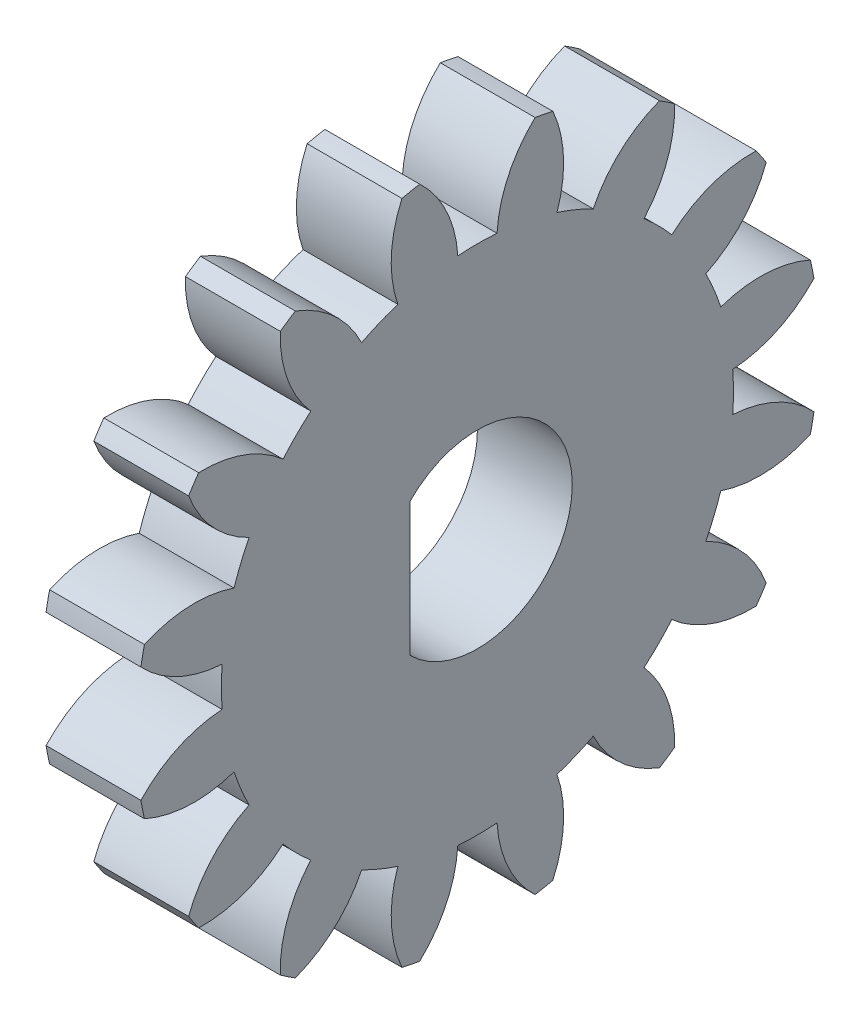
SolidWorks part; units mm, degrees
ref_plane "Plane1" through (0, 0, 0) normal (0, 0, 1) x (1, 0, 0)
ref_plane "Plane2" through (0, 0, 0) normal (0, 1, 0) x (1, 0, 0)
ref_plane "Plane3" through (0, 0, 0) normal (1, 0, 0) x (0, 0, -1)
other "Configuration Table"
sketch "HoldingSke" plane through (0, 0, 0) normal (0, 1, 0) x (1, 0, 0)
  line L0 (0, 0) -> (0.4806, -0.1378)
  line L1 (-15, 0) -> (100, 0) construction
  line L2 (0, 0) -> (-2.1039, 2.3779)
  line L3 (0, 0) -> (-11.863, 4.5341)
  line L4 (0, 0) -> (8.3015, 2.3804)
  line L5 (0, 0) -> (-46.8476, -17.4728)
  line L6 (0, 0) -> (-4.1448, -2.7965)
  line L7 (-2.1039, 2.3779) -> (8.6586, 51.2059)
  line L8 (-76.2, 54.61) -> (-74.4, 54.61)
  line L9 (-71.009, 38.7566) -> (-53.1078, 45.2721)
  line L10 (-76.2, 71.12) -> (104.1128, 71.12)
  line L11 (0, 0) -> (-5, 0)
  line L12 (-76.2, 101.6) -> (-76.133, 101.6)
  line L13 (24.9733, 27.94) -> (52.9518, 28.4284)
  line L14 (24.9733, 27.94) -> (24.9743, 27.94)
  line L15 (24.9733, 27.94) -> (100.4006, 29.5858)
  line L16 (-63.627, -2) -> (-12.827, -2)
  circle A0 centre (0, 0) radius 5
  circle A1 centre (0, 0) radius 13.499
  circle A2 centre (0, 0) radius 37.5
  circle A3 centre (0, 0) radius 5
  dimension "MHD" = 26.998
  dimension "Hub_dia" = 75
  dimension "Bore" = 10
  dimension "MBD" = 10
  dimension "Num_teeth" = 16
  dimension "Pitch" = 0.5
  dimension "Overall_len" = 50
  dimension "Show_teeth" = 16
  dimension "Thickness" = 5
  dimension "OAL" = 50.0001
  dimension "T_dim" = 1.8
  dimension "Ap" = 20
  dimension "H" = 19.05
  dimension "Pitch_radius" = 180.3128
  dimension "Width" = 5
  dimension "Backlash" = 0.067
  dimension "Addendum_fac" = 1
  dimension "Dedendum_fac" = 1.25
  dimension "Clearance_fac" = 0.25
  dimension "Dedendum_add" = 0.001
  dimension "Module" = 2
sketch "BasProSke" plane through (0, 0, 0) normal (0, 1, 0) x (1, 0, 0)
  line L0 (-10, 0) -> (60, 0) construction
  line L1 (0, 0) -> (0, 18)
  line L2 (0, 0) -> (5, 0)
  line L3 (5, 0) -> (5, 18)
  line L4 (5, 18) -> (0, 18)
  dimension "Thickness" = 5
  dimension "Diameter" = 36
revolve "Base-Revolve" add sketch "BasProSke" angle 360 about L0
sketch "TooCutSke" plane through (0, 0, 0) normal (1, 0, 0) x (0, 0, -1)
  line L1 (0, 0) -> (0, 107) construction
  line L2 (0, 0) -> (-1.6854, 15.911) construction
  line L3 (0, 0) -> (-6.2172, 31.2558) construction
  line L4 (-1.6854, 15.911) -> (-3.1086, 15.6279) construction
  arc A0 (1.0343, 13.4593) -> (-1.0343, 13.4593) centre (0, 0) ccw
  arc A1 (3.0657, 17.7628) -> (-3.0657, 17.7628) centre (0, 0) ccw
  circle A2 centre (0, 0) radius 16 construction
  circle A3 centre (0, 0) radius 15.0351 construction
  arc A4 (-1.0343, 13.4593) -> (-3.0657, 17.7628) centre (-7.4228, 13.075) ccw
  arc A5 (3.0657, 17.7628) -> (1.0343, 13.4593) centre (7.4228, 13.075) ccw
  dimension "Root_dia" = 26.998
  dimension "Overcut_dia" = 36.0508
  dimension "Pitch_dia" = 32
  dimension "Base_dia" = 30.0702
  dimension "Flank_rad" = 6.4
  dimension "Half_ang" = 11.25
  dimension "Half_CT" = 1.451
extrude "ToothCut" cut sketch "TooCutSke" along normal through all
fillet "Breaks" [suppressed] radius 0.04
fillet "RootFillets" [suppressed] radius 0.501
pattern_circular "TeethCuts" count 16 every 22.5 about axis through (-10, 0, 0) along (1, 0, 0) of "ToothCut", "RootFillets", "Breaks"
sketch "HubNeaOneSke" plane through (0, 0, 0) normal (-1, 0, 0) x (0, 0, 1)
  circle A0 centre (0, 0) radius 13.499
  dimension "Diameter" = 26.998
extrude "HubNearOne" [suppressed] add sketch "HubNeaOneSke" along normal blind 45.0001
sketch "HubNeaBotSke" plane through (0, 0, 0) normal (-1, 0, 0) x (0, 0, 1)
  circle A0 centre (0, 0) radius 13.499
  dimension "Diameter" = 26.998
extrude "HubNearBoth" [suppressed] add sketch "HubNeaBotSke" along normal blind 22.5
ref_plane "FarPln" through (5, 0, 0) normal (1, 0, 0) x (0, 0, -1)
sketch "HubFarSke" plane through (5, 0, 0) normal (1, 0, 0) x (0, 0, -1)
  circle A0 centre (0, 0) radius 13.499
  dimension "Diameter" = 26.998
extrude "HubFar" [suppressed] add sketch "HubFarSke" along normal blind 22.5
sketch "BorSke" plane through (0, 0, 0) normal (1, 0, 0) x (0, 0, -1)
  circle A0 centre (0, 0) radius 5
  dimension "Diameter" = 10
extrude "Bore" cut sketch "BorSke" along normal mid plane 100.0001
sketch "KeySke" plane through (0, 0, 0) normal (1, 0, 0) x (0, 0, -1)
  line L0 (-2, 0) -> (-2, 6.8)
  line L1 (-2, 6.8) -> (2, 6.8)
  line L2 (2, 6.8) -> (2, 0)
  line L3 (0, 0) -> (0, 34) construction
  line L4 (-2, 0) -> (2, 0)
  dimension "Offset" = 6.8
  dimension "Width" = 4
extrude "Keyway" [suppressed] cut sketch "KeySke" along normal mid plane 100.0001
pattern_circular "Keyway2" [suppressed] count 2 every 90 about axis through (-10, 0, 0) along (1, 0, 0)
sketch "草图2" plane through (0, 0, 0) normal (-1, 0, 0) x (0, 0, 1)
  line L0 (3.5448, 3.5262) -> (3.5448, -3.5262)
  arc A0 (3.5448, -3.5262) -> (3.5448, 3.5262) centre (0, 0) ccw
extrude "凸台-拉伸1" add sketch "草图2" against normal up to surface (5 mm away) up to face at (5, 0, 5)
equation "' \"Module@HoldingSke\" = 6.35"
equation "' \"Num_teeth@HoldingSke\" = 12"
equation "' \"Ap@HoldingSke\" =  20"
equation "' \"Ap@HoldingSke\" = 20"
equation "' \"Width@HoldingSke\" = 0.5 * 25.4"
equation "' \"Hub_dia@HoldingSke\"= 1 * 25.4"
equation "' \"Hub_dia@HoldingSke\" = 1 * 25.4"
equation "' \"Overall_len@HoldingSke\" = 1.0 * 25.4"
equation "' \"Bore@HoldingSke\" = 0.75 * 25.4"
equation "' \"T_dim@HoldingSke\" = 0.1 * 25.4"
equation "' \"Width@KeySke\" = 0.25 * 25.4"
equation "' \"Show_teeth@HoldingSke\" = 13"
equation "' \"Backlash@HoldingSke\" = 0.009 * 25.4"
equation "' \"Addendum_fac@HoldingSke\" = 1.0"
equation "' \"Dedendum_fac@HoldingSke\" = 1.25"
equation "' \"Dedendum_add@HoldingSke\" = 0.00005 * 25.4"
equation "' \"Clearance_fac@HoldingSke\" = 0.25"
equation "\"Pitch@HoldingSke\" = 1 / \"Module@HoldingSke\""
equation "\"Overcut_dia@TooCutSke\" = (\"Num_teeth@HoldingSke\" + 2 * \"Addendum_fac@HoldingSke\") / \"Pitch@HoldingSke\" + 0.002 * 25.4"
equation "\"Pitch_dia@TooCutSke\" = \"Num_teeth@HoldingSke\" / \"Pitch@HoldingSke\""
equation "\"Base_dia@TooCutSke\" = \"Num_teeth@HoldingSke\" / \"Pitch@HoldingSke\" * cos((\"Ap@HoldingSke\"  * 3.14159265 / 180))"
equation "\"Root_dia@TooCutSke\" = (\"Num_teeth@HoldingSke\" + 2) / \"Pitch@HoldingSke\" - 2 * (\"Addendum_fac@HoldingSke\" + \"Dedendum_fac@HoldingSke\") / \"Pitch@HoldingSke\" - \"Dedendum_add@HoldingSke\" * 2"
equation "\"Half_ang@TooCutSke\" = 180 / \"Num_teeth@HoldingSke\""
equation "\"Half_CT@TooCutSke\" = \"Num_teeth@HoldingSke\" / \"Pitch@HoldingSke\" * sin((3.14159265 / 2 / \"Num_teeth@HoldingSke\")) / 2 - 7 * \"Backlash@HoldingSke\" / 4"
equation "\"Flank_rad@TooCutSke\" = \"Num_teeth@HoldingSke\" / \"Pitch@HoldingSke\" / 5"
equation "\"Radius@RootFillets\" = \"Clearance_fac@HoldingSke\" / \"Pitch@HoldingSke\" + \"Dedendum_add@HoldingSke\""
equation "\"Break_rad@Breaks\" = 0.02 / \"Pitch@HoldingSke\""
equation "\"Thickness@HoldingSke\" = \"Width@HoldingSke\""
equation "\"OAL@HoldingSke\" = \"Thickness@HoldingSke\""
equation "\"MHD@HoldingSke\" = (\"Num_teeth@HoldingSke\" + 2) / \"Pitch@HoldingSke\" - 2 * (\"Addendum_fac@HoldingSke\" + \"Dedendum_fac@HoldingSke\")  / \"Pitch@HoldingSke\" - \"Dedendum_add@HoldingSke\" * 2"
equation "\"MBD@HoldingSke\" = (\"Num_teeth@HoldingSke\" + 2) / \"Pitch@HoldingSke\" - 2 * (\"Addendum_fac@HoldingSke\" + \"Dedendum_fac@HoldingSke\")  / \"Pitch@HoldingSke\" - \"Dedendum_add@HoldingSke\" * 2 - 0.002 * 25.4"
equation "\"MHD@HoldingSke\" = ((sgn( \"MHD@HoldingSke\" - \"Hub_dia@HoldingSke\" )-1)*( \"MHD@HoldingSke\" - \"Hub_dia@HoldingSke\" ))/-2+ \"Hub_dia@HoldingSke\""
equation "\"MBD@HoldingSke\" = ((sgn( \"MBD@HoldingSke\" - \"Bore@HoldingSke\" )-1)*( \"MBD@HoldingSke\" - \"Bore@HoldingSke\" ))/-2+ \"Bore@HoldingSke\""
equation "\"OAL@HoldingSke\" = ((sgn( \"OAL@HoldingSke\" - \"Overall_len@HoldingSke\" )+1)*( \"OAL@HoldingSke\" - \"Overall_len@HoldingSke\" ))/2 + \"Overall_len@HoldingSke\" + 0.000002 * 25.4"
equation "\"Num_teeth@TeethCuts\" = int( \"Show_teeth@HoldingSke\" ) + 1"
equation "\"Num_teeth@TeethCuts\" = ((sgn( \"Num_teeth@TeethCuts\" - \"Num_teeth@HoldingSke\" )-1)*( \"Num_teeth@TeethCuts\" - \"Num_teeth@HoldingSke\" ))/-2+ \"Num_teeth@HoldingSke\""
equation "\"Num_teeth@TeethCuts\" = ((sgn( \"Num_teeth@TeethCuts\" - 2.0)+1)*( \"Num_teeth@TeethCuts\" - 2.0))/2 +2.0"
equation "\"Angle@TeethCuts\" = 360.0 / \"Num_teeth@HoldingSke\""
equation "\"Diameter@BasProSke\" = (\"Num_teeth@HoldingSke\" + 2 * \"Addendum_fac@HoldingSke\") / \"Pitch@HoldingSke\""
equation "\"Thickness@BasProSke\"  = \"Thickness@HoldingSke\""
equation "' \"Fillet_rad@BasProSke\" =  \"Thickness@HoldingSke\" * 0.05"
equation "' \"Fillet_rad@BasProSke\" = \"Thickness@HoldingSke\" * 0.05"
equation "\"MHD@HoldingSke\" = ((sgn( \"MHD@HoldingSke\" - \"Root_dia@TooCutSke\" )-1)*( \"MHD@HoldingSke\" - \"Root_dia@TooCutSke\" ))/-2+ \"Root_dia@TooCutSke\""
equation "\"Diameter@HubNeaOneSke\" = \"MHD@HoldingSke\""
equation "\"Length@HubNearOne\" = \"OAL@HoldingSke\" - \"Thickness@BasProSke\""
equation "\"Diameter@HubNeaBotSke\" = \"MHD@HoldingSke\""
equation "\"Length@HubNearBoth\" = ( \"OAL@HoldingSke\" - \"Thickness@BasProSke\" ) / 2.0"
equation "\"Thickness@FarPln\" = \"Thickness@BasProSke\""
equation "\"Diameter@HubFarSke\" = \"MHD@HoldingSke\""
equation "\"Length@HubFar\" = ( \"OAL@HoldingSke\" - \"Thickness@BasProSke\" ) / 2.0"
equation "\"Diameter@BorSke\" = \"MBD@HoldingSke\""
equation "\"D1@Bore\" = \"OAL@HoldingSke\" * 2.0"
equation "\"D1@Keyway\" = \"OAL@HoldingSke\" * 2.0"
equation "\"Offset@KeySke\" = \"T_dim@HoldingSke\" + \"MBD@HoldingSke\" / 2.0"
